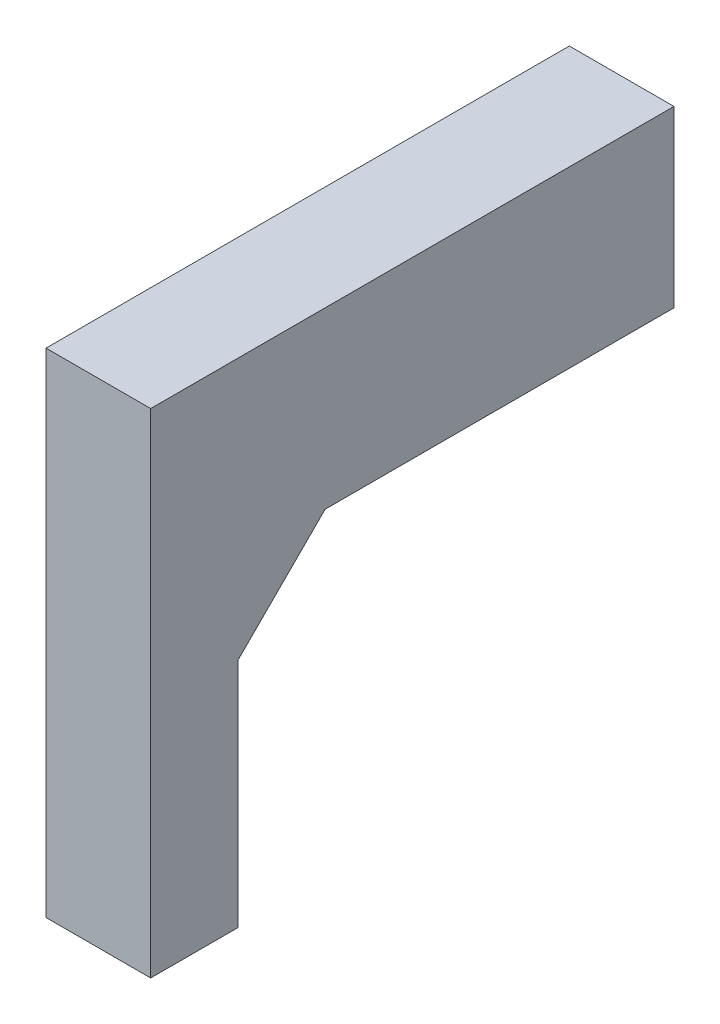
SolidWorks part; units mm, degrees
ref_plane "Front Plane" through (0, 0, 0) normal (1, 0, 0) x (0, 1, 0)
ref_plane "Top Plane" through (0, 0, 0) normal (0, 0, 1) x (0, 1, 0)
ref_plane "Right Plane" through (0, 0, 0) normal (0, 1, 0) x (-1, 0, 0)
sketch "Sketch1" plane through (0, 0, 0) normal (1, 0, 0) x (0, 1, 0)
  line L0 (0, 0) -> (-50, 0)
  line L1 (-50, 0) -> (-50, 100)
  line L2 (0, 0) -> (0, 150)
  line L3 (-50, 100) -> (-74.9609, 124.9609)
  line L4 (-74.9609, 124.9609) -> (-141.3609, 124.9609)
  line L5 (-141.3609, 124.9609) -> (-141.3609, 150)
  line L6 (-141.3609, 150) -> (0, 150)
  dimension "D1" = 50
  dimension "D2" = 100
  dimension "D3" = 150
  dimension "D4" = 35.3
  dimension "D5" = 66.4
extrude "Boss-Extrude1" add sketch "Sketch1" along normal blind 30 contours L4 L5 L6 L2 L0 L1 L3
